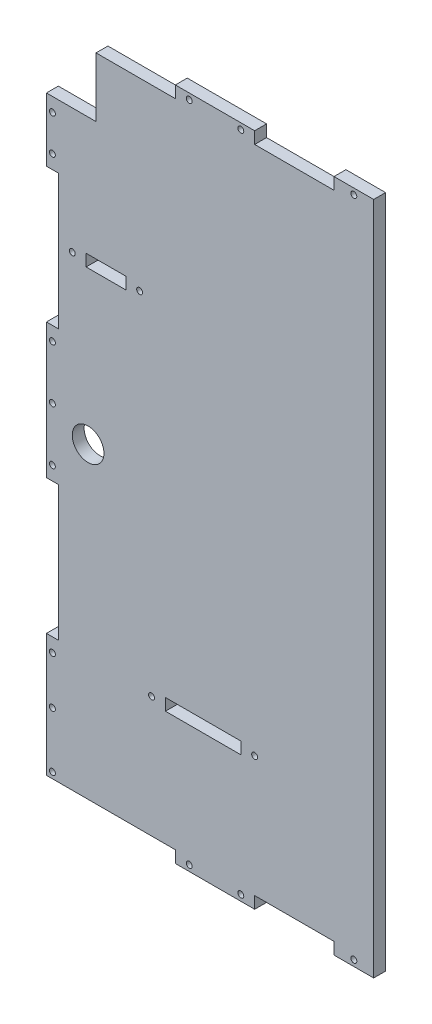
SolidWorks part; units mm, degrees
ref_plane "Plan de face" through (0, 0, 0) normal (0, 0, 1) x (1, 0, 0)
ref_plane "Plan de dessus" through (0, 0, 0) normal (0, 1, 0) x (1, 0, 0)
ref_plane "Plan de droite" through (0, 0, 0) normal (1, 0, 0) x (0, 0, -1)
sketch "Esquisse2" plane through (0, 0, 0) normal (0, 0, 1) x (1, 0, 0)
  line L1 (0, 0) -> (-330, 0)
  line L2 (0, 0) -> (0, -340)
  line L3 (0, -340) -> (-330, -340)
  line L4 (-330, 0) -> (-330, -340)
  dimension "D1" = 340
  dimension "D2" = 330
extrude "Boss.-Extru.1" add sketch "Esquisse2" along normal blind 6
sketch "Esquisse4" plane through (0, 0, 0) normal (0, 0, -1) x (-1, 0, 0)
  line L0 (0, 0) -> (330, 0) construction
  line L1 (330, 0) -> (265, 0)
  line L2 (330, 0) -> (330, -6)
  line L3 (330, -6) -> (265, -6)
  line L4 (265, 0) -> (265, -6)
  line L5 (225, 0) -> (185, 0)
  line L6 (225, 0) -> (225, -6)
  line L7 (225, -6) -> (185, -6)
  line L8 (185, 0) -> (185, -6)
  line L9 (330, 0) -> (330, -340) construction
  line L10 (145, 0) -> (105, 0)
  line L11 (145, 0) -> (145, -6)
  line L12 (145, -6) -> (105, -6)
  line L13 (105, 0) -> (105, -6)
  line L14 (0, 0) -> (65, 0)
  line L15 (0, 0) -> (0, -6)
  line L16 (0, -6) -> (65, -6)
  line L17 (65, 0) -> (65, -6)
  line L19 (330, -68) -> (324, -68)
  line L20 (330, -68) -> (330, -136)
  line L21 (330, -136) -> (324, -136)
  line L22 (330, -340) -> (0, -340) construction
  line L23 (324, -68) -> (324, -136)
  line L24 (0, -136) -> (6, -136)
  line L25 (0, -136) -> (0, -68)
  line L26 (0, -68) -> (6, -68)
  line L27 (330, -340) -> (265, -340)
  line L28 (330, -340) -> (330, -334)
  line L29 (330, -334) -> (265, -334)
  line L30 (265, -340) -> (265, -334)
  line L31 (225, -340) -> (185, -340)
  line L32 (225, -340) -> (225, -334)
  line L33 (225, -334) -> (185, -334)
  line L34 (185, -340) -> (185, -334)
  line L35 (0, -340) -> (0, 0) construction
  line L36 (145, -340) -> (105, -340)
  line L37 (145, -340) -> (145, -334)
  line L38 (145, -334) -> (105, -334)
  line L39 (105, -340) -> (105, -334)
  line L40 (65, -340) -> (0, -340)
  line L41 (65, -340) -> (65, -334)
  line L42 (65, -334) -> (0, -334)
  line L43 (0, -340) -> (0, -334)
  line L44 (330, -204) -> (324, -204)
  line L45 (330, -204) -> (330, -272)
  line L46 (330, -272) -> (324, -272)
  line L47 (324, -204) -> (324, -272)
  line L48 (6, -136) -> (6, -68)
  line L52 (0, -204) -> (6, -204)
  line L53 (0, -204) -> (0, -272)
  line L54 (0, -272) -> (6, -272)
  line L55 (6, -204) -> (6, -272)
  dimension "D1" = 6
  dimension "D2" = 65
  dimension "D3" = 40
  dimension "D4" = 6
  dimension "D5" = 40
  dimension "D6" = 40
  dimension "D7" = 6
  dimension "D8" = 40
  dimension "D9" = 40
  dimension "D10" = 6
  dimension "D11" = 68
  dimension "D12" = 6
  dimension "D13" = 68
  dimension "D14" = 68
  dimension "D15" = 65
  dimension "D16" = 6
  dimension "D17" = 6
  dimension "D18" = 40
  dimension "D19" = 40
  dimension "D20" = 40
  dimension "D21" = 40
  dimension "D22" = 6
  dimension "D23" = 65
  dimension "D24" = 40
  dimension "D25" = 6
  dimension "D26" = 68
  dimension "D27" = 68
  dimension "D28" = 68
  dimension "D29" = 68
  dimension "D30" = 6
  dimension "D31" = 6
  dimension "D32" = 68
  dimension "D34" = 6
extrude "Enlèv. mat encoche bord" cut sketch "Esquisse4" against normal through all
sketch "Esquisse5" plane through (0, 0, 0) normal (0, 0, -1) x (-1, 0, 0)
  line L0 (265, -340) -> (225, -340) construction
  line L1 (270, -276) -> (232, -276)
  line L2 (270, -276) -> (270, -270)
  line L3 (270, -270) -> (232, -270)
  line L4 (232, -276) -> (232, -270)
  line L5 (98, -276) -> (60, -276)
  line L6 (98, -276) -> (98, -270)
  line L7 (98, -270) -> (60, -270)
  line L8 (60, -276) -> (60, -270)
  line L9 (330, -6) -> (305, -6)
  line L10 (330, -6) -> (330, -36)
  line L11 (330, -36) -> (305, -36)
  line L12 (305, -6) -> (305, -36)
  line L13 (0, -6) -> (15, -6)
  line L14 (0, -6) -> (0, -16)
  line L15 (0, -16) -> (15, -16)
  line L16 (15, -6) -> (15, -16)
  line L17 (310, -102) -> (290, -102)
  line L19 (0, -68) -> (0, -6) construction
  line L20 (330, -272) -> (330, -334) construction
  line L21 (310, -102) -> (310, -96)
  line L22 (310, -96) -> (290, -96)
  line L23 (290, -102) -> (290, -96)
  line L24 (40, -102) -> (20, -102)
  line L25 (40, -102) -> (40, -96)
  line L26 (40, -96) -> (20, -96)
  line L27 (20, -102) -> (20, -96)
  line L30 (105, -340) -> (65, -340) construction
  line L31 (225, 0) -> (265, 0) construction
  line L32 (65, 0) -> (105, 0) construction
  dimension "D1" = 6
  dimension "D2" = 38
  dimension "D3" = 38
  dimension "D4" = 6
  dimension "D5" = 134
  dimension "D6" = 60
  dimension "D7" = 30
  dimension "D8" = 70
  dimension "D9" = 102
  dimension "D10" = 25
  dimension "D11" = 10
  dimension "D12" = 15
  dimension "D13" = 20
  dimension "D14" = 102
  dimension "D15" = 6
  dimension "D16" = 6
  dimension "D17" = 20
  dimension "D18" = 70
  dimension "D19" = 20
  dimension "D20" = 20
extrude "Enlèv. mat encoche étage + roulettes" cut sketch "Esquisse5" against normal through all
sketch "Esquisse6" plane through (0, 0, 6) normal (0, 0, 1) x (1, 0, 0)
  line L0 (-105, -340) -> (-65, -340) construction
  line L1 (0, -204) -> (0, -136) construction
  line L2 (-330, -136) -> (-330, -204) construction
  line L3 (-265, -340) -> (-225, -340) construction
  line L4 (-330, -204) -> (-324, -204) construction
  circle A0 centre (-21, -178.92) radius 8
  circle A1 centre (-309, -178.92) radius 8
  dimension "D3" = 16
  dimension "D4" = 16
  dimension "D1" = 161.08
  dimension "D2" = 21
  dimension "D5" = 21
  dimension "D6" = 161.08
extrude "Enlèv. mat.-Extru.1" cut sketch "Esquisse6" against normal blind 10
sketch "Esquisse7" plane through (0, 0, 6) normal (0, 0, 1) x (1, 0, 0)
  line L0 (-145, 0) -> (-185, 0) construction
  line L1 (-165, 0) -> (0, 0)
  line L2 (-165, 0) -> (-165, -340.8617)
  line L3 (-165, -340.8617) -> (0, -340.8617)
  line L4 (0, 0) -> (0, -340.8617)
extrude "Enlèv. mat.-Extru.2" cut sketch "Esquisse7" against normal through all
sketch "Esquisse8" plane through (0, 0, 0) normal (0, 0, -1) x (-1, 0, 0)
  line L2 (330, -334) -> (265, -334) construction
  line L3 (330, -272) -> (330, -334) construction
  line L4 (324, -272) -> (330, -272) construction
  line L5 (265, -340) -> (225, -340) construction
  line L6 (265, -334) -> (265, -340) construction
  line L7 (225, -340) -> (225, -334) construction
  line L8 (185, -340) -> (165, -340) construction
  line L9 (185, -334) -> (185, -340) construction
  line L10 (330, -136) -> (330, -204) construction
  line L11 (330, -204) -> (324, -204) construction
  line L12 (324, -136) -> (330, -136) construction
  line L13 (330, -68) -> (324, -68) construction
  line L14 (330, -36) -> (330, -68) construction
  line L15 (305, -36) -> (330, -36) construction
  line L16 (265, 0) -> (265, -6) construction
  line L17 (225, 0) -> (265, 0) construction
  line L18 (225, -6) -> (225, 0) construction
  line L19 (185, 0) -> (185, -6) construction
  line L20 (165, 0) -> (185, 0) construction
  line L21 (310, -102) -> (310, -96) construction
  line L22 (310, -96) -> (290, -96) construction
  line L23 (290, -96) -> (290, -102) construction
  line L24 (232, -270) -> (232, -276) construction
  line L25 (270, -270) -> (232, -270) construction
  line L26 (270, -276) -> (270, -270) construction
  line L27 (232, -276) -> (270, -276) construction
  circle A0 centre (175, -337) radius 1.5
  circle A1 centre (232, -337) radius 1.5
  circle A2 centre (258, -337) radius 1.5
  circle A3 centre (327, -331) radius 1.5
  circle A4 centre (327, -303) radius 1.5
  circle A5 centre (327, -279) radius 1.5
  circle A6 centre (277, -273) radius 1.5
  circle A7 centre (225, -273) radius 1.5
  circle A8 centre (327, -197) radius 1.5
  circle A9 centre (327, -170) radius 1.5
  circle A10 centre (327, -143) radius 1.5
  circle A11 centre (327, -61) radius 1.5
  circle A12 centre (327, -43) radius 1.5
  circle A13 centre (258, -3) radius 1.5
  circle A14 centre (232, -3) radius 1.5
  circle A15 centre (175, -3) radius 1.5
  circle A16 centre (317, -99) radius 1.5
  circle A17 centre (283, -99) radius 1.5
  point P40 (327, -272)
  point P55 (327, -204)
  point P58 (327, -136)
  point P61 (327, -136)
  point P62 (330, -170)
  point P73 (225, -3)
  dimension "D1" = 3
  dimension "D2" = 3
  dimension "D3" = 3
  dimension "D4" = 3
  dimension "D6" = 7
  dimension "D7" = 3
  dimension "D9" = 31
  dimension "D10" = 3
  dimension "D11" = 3
  dimension "D12" = 7
  dimension "D13" = 3
  dimension "D14" = 3
  dimension "D15" = 7
  dimension "D16" = 3
  dimension "D18" = 10
  dimension "D19" = 3
  dimension "D20" = 3
  dimension "D21" = 3
  dimension "D22" = 7
  dimension "D23" = 3
  dimension "D24" = 3
  dimension "D25" = 7
  dimension "D26" = 34
  dimension "D28" = 3
  dimension "D29" = 3
  dimension "D32" = 3
  dimension "D33" = 7
  dimension "D34" = 3
  dimension "D35" = 7
  dimension "D36" = 3
  dimension "D37" = 3
  dimension "D38" = 7
  dimension "D39" = 3
  dimension "D40" = 3
  dimension "D41" = 10
  dimension "D43" = 3
  dimension "D44" = 7
  dimension "D46" = 3
  dimension "D47" = 7
  dimension "D48" = 3
  dimension "D49" = 3
  dimension "D50" = 7
  dimension "D51" = 3
  dimension "D52" = 3
  dimension "D53" = 3
  dimension "D54" = 7
  dimension "D5" = 3
  dimension "D8" = 3
  dimension "D17" = 3
  dimension "D27" = 3
  dimension "D30" = 7
  dimension "D31" = 3
  dimension "D42" = 3
  dimension "D45" = 3
extrude "Enlèv. mat.-Extru.3" cut sketch "Esquisse8" against normal through all
sketch "Esquisse9" plane through (0, 0, 0) normal (0, 0, -1) x (-1, 0, 0)
  circle A0 centre (327, -43) radius 2.995
  circle A1 centre (327, -61) radius 2.995
  circle A2 centre (317, -99) radius 2.995
  circle A3 centre (283, -99) radius 2.995
  circle A4 centre (327, -143) radius 2.995
  circle A5 centre (327, -170) radius 2.995
  circle A6 centre (327, -331) radius 2.995
  circle A8 centre (327, -303) radius 2.995
  circle A9 centre (327, -279) radius 2.995
  circle A10 centre (277, -273) radius 3
  circle A11 centre (225, -273) radius 3
  circle A12 centre (258, -337) radius 2.995
  circle A13 centre (232, -337) radius 2.995
  circle A14 centre (175, -337) radius 2.995
  circle A15 centre (327, -197) radius 2.995
  circle A16 centre (258, -3) radius 2.995
  circle A17 centre (232, -3) radius 2.995
  circle A18 centre (175, -3) radius 2.995
  dimension "D1" = 5.99
  dimension "D2" = 5.99
  dimension "D3" = 5.99
  dimension "D4" = 5.99
  dimension "D5" = 5.99
  dimension "D6" = 5.99
  dimension "D7" = 5.99
  dimension "D8" = 5.99
  dimension "D9" = 5.99
  dimension "D10" = 5.99
  dimension "D11" = 5.99
  dimension "D12" = 5.99
  dimension "D13" = 5.99
  dimension "D14" = 6
  dimension "D15" = 6
  dimension "D16" = 5.99
  dimension "D17" = 5.99
  dimension "D18" = 5.99
extrude "Enlèv. mat.-Extru.4" cut sketch "Esquisse9" against normal blind 3
sketch "Esquisse10" plane through (0, 0, 0) normal (0, 0, -1) x (-1, 0, 0)
  line L0 (165, 0) -> (165, -340) construction
  line L1 (165, -266.0231) -> (337.8305, -266.0231)
  line L2 (165, -266.0231) -> (165, -342.5863)
  line L3 (165, -342.5863) -> (337.8305, -342.5863)
  line L4 (337.8305, -266.0231) -> (337.8305, -342.5863)
